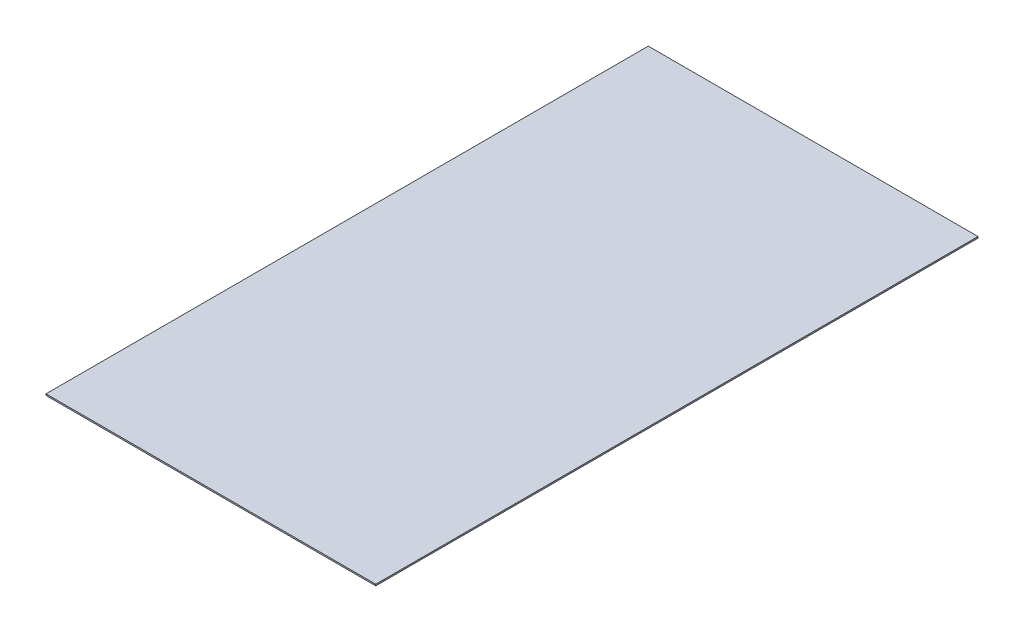
SolidWorks part; units mm, degrees
ref_plane "Front Plane" through (0, 0, 0) normal (0, 0, 1) x (1, 0, 0)
ref_plane "Top Plane" through (0, 0, 0) normal (0, 1, 0) x (1, 0, 0)
ref_plane "Right Plane" through (0, 0, 0) normal (1, 0, 0) x (0, 0, -1)
sketch "Sketch1" plane through (0, 0, 0) normal (0, 1, 0) x (1, 0, 0)
  line L0 (-2133.6, 3943.35) -> (2184.4, 3943.35)
  line L1 (-2133.6, -3943.35) -> (2184.4, -3943.35)
  line L2 (2184.4, -3943.35) -> (2184.4, 3943.35)
  line L6 (-2133.6, 3943.35) -> (-2133.6, -3943.35)
extrude "Boss-Extrude1" add sketch "Sketch1" along normal blind 19.05
